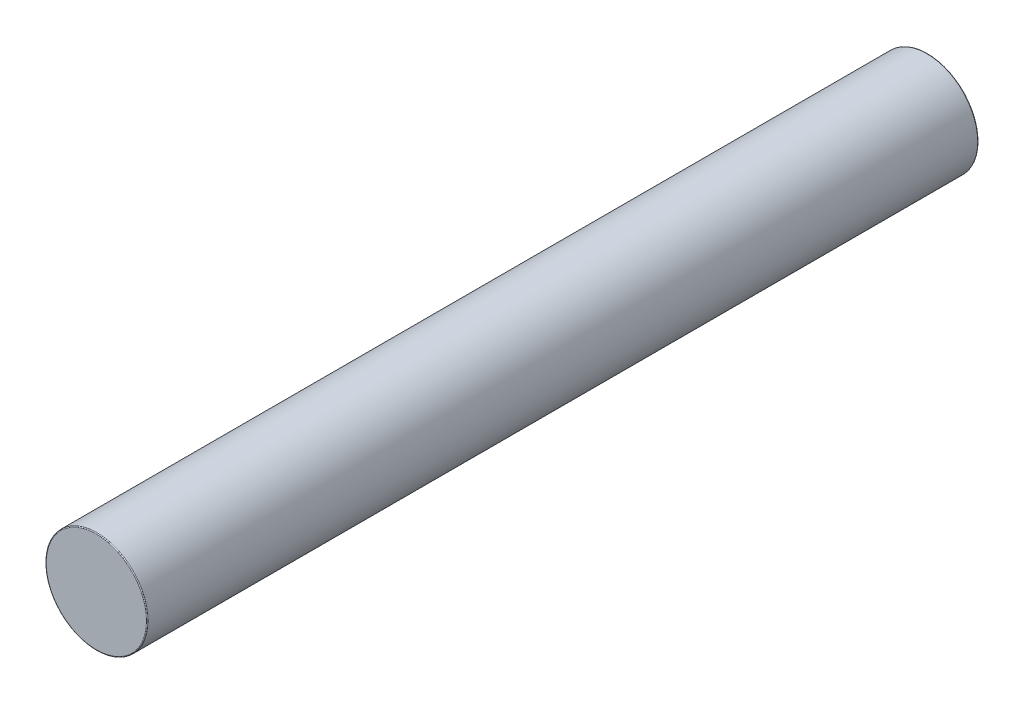
SolidWorks part; units mm, degrees
ref_plane "Alzado" through (0, 0, 0) normal (0, 0, 1) x (1, 0, 0)
ref_plane "Planta" through (0, 0, 0) normal (0, 1, 0) x (1, 0, 0)
ref_plane "Vista lateral" through (0, 0, 0) normal (1, 0, 0) x (0, 0, -1)
sketch "Croquis1" plane through (0, 0, 0) normal (0, 0, 1) x (1, 0, 0)
  circle A0 centre (0, 0) radius 1.225
  dimension "D1" = 2.45
extrude "Saliente-Extruir1" add sketch "Croquis1" along normal blind 20
fillet "Redondeo1" radius 0.02 2 edges at (1.225, 0, 0) (1.225, 0, 20)
